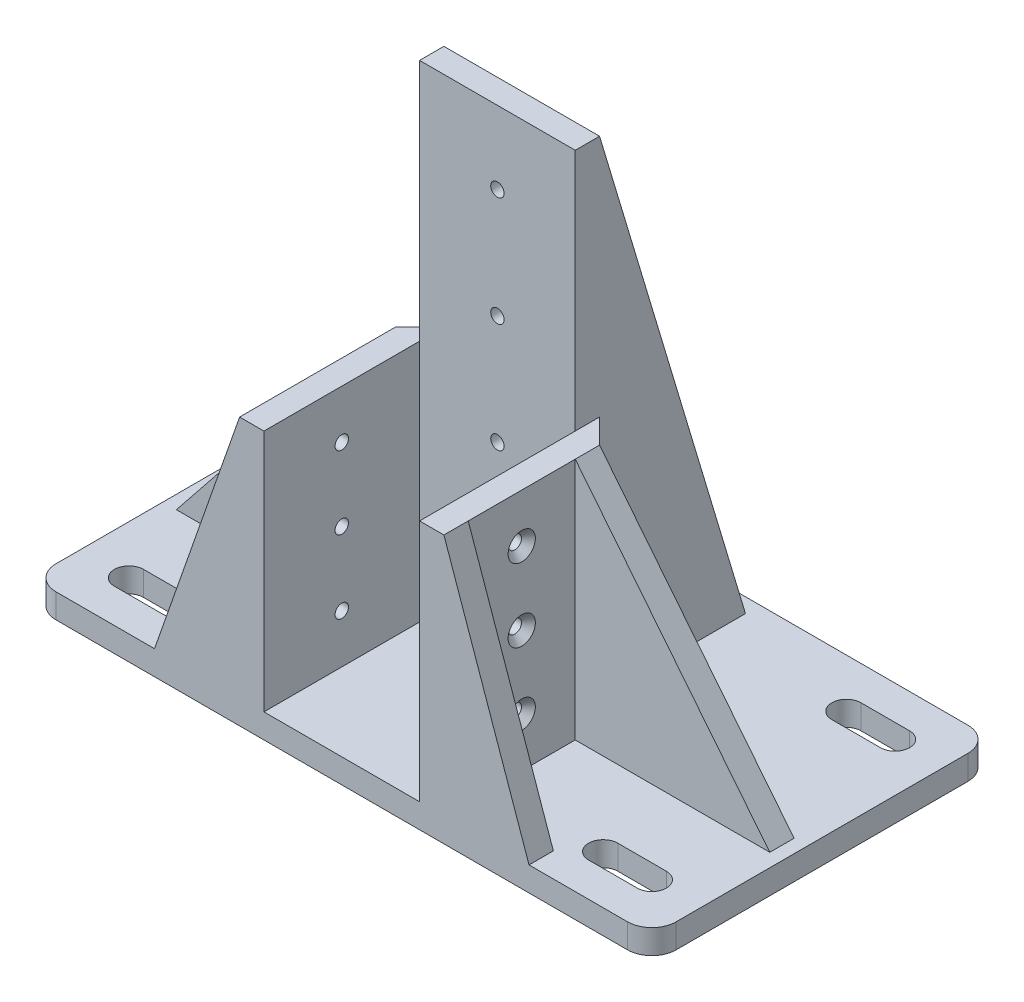
SolidWorks part; units mm, degrees
material "1060 合金"
ref_plane "前视基准面" through (0, 0, 0) normal (0, 0, 1) x (1, 0, 0)
ref_plane "上视基准面" through (0, 0, 0) normal (0, 1, 0) x (1, 0, 0)
ref_plane "右视基准面" through (0, 0, 0) normal (1, 0, 0) x (0, 0, -1)
sketch "草图1" plane through (0, 0, 0) normal (0, 1, 0) x (1, 0, 0)
  line L0 (-107.5, 50) -> (-87.5, 50) construction
  line L1 (-117.5, 70) -> (117.5, 70)
  line L2 (-127.5, 60) -> (-127.5, -60)
  line L3 (-117.5, -70) -> (117.5, -70)
  line L4 (127.5, 60) -> (127.5, -60)
  line L7 (-107.5, 56) -> (-87.5, 56)
  line L8 (-107.5, 44) -> (-87.5, 44)
  line L9 (0, 0) -> (-135, 0) construction
  line L10 (-107.5, -50) -> (-87.5, -50) construction
  line L11 (-107.5, -56) -> (-87.5, -56)
  line L12 (-107.5, -44) -> (-87.5, -44)
  line L13 (0, 0) -> (0, -60) construction
  line L14 (107.5, -50) -> (87.5, -50) construction
  line L15 (107.5, -56) -> (87.5, -56)
  line L16 (107.5, -44) -> (87.5, -44)
  line L17 (107.5, 50) -> (87.5, 50) construction
  line L18 (107.5, 56) -> (87.5, 56)
  line L19 (107.5, 44) -> (87.5, 44)
  arc A0 (-107.5, 56) -> (-107.5, 44) centre (-107.5, 50) ccw
  arc A1 (-87.5, 44) -> (-87.5, 56) centre (-87.5, 50) ccw
  arc A2 (-107.5, -56) -> (-107.5, -44) centre (-107.5, -50) cw
  arc A3 (-87.5, -44) -> (-87.5, -56) centre (-87.5, -50) cw
  arc A4 (107.5, -56) -> (107.5, -44) centre (107.5, -50) ccw
  arc A5 (87.5, -44) -> (87.5, -56) centre (87.5, -50) ccw
  arc A6 (107.5, 56) -> (107.5, 44) centre (107.5, 50) cw
  arc A7 (87.5, 44) -> (87.5, 56) centre (87.5, 50) cw
  arc A8 (117.5, 70) -> (127.5, 60) centre (117.5, 60) cw
  arc A9 (117.5, -70) -> (127.5, -60) centre (117.5, -60) ccw
  arc A10 (-127.5, -60) -> (-117.5, -70) centre (-117.5, -60) ccw
  arc A11 (-117.5, 70) -> (-127.5, 60) centre (-117.5, 60) ccw
  point P0 (0, 0)
  point P8 (-97.5, 50)
  point P17 (-97.5, -50)
  point P26 (97.5, -50)
  point P33 (97.5, 50)
  point P50 (0, 0)
  dimension "D3" = 6
  dimension "D5" = 20
  dimension "D7" = 10
  dimension "D9" = 20
  dimension "D8" = 20
  dimension "D1" = 100
  dimension "D2" = 175
  dimension "D4" = 20
  dimension "D6" = 20
extrude "立臂底座" add sketch "草图1" along normal blind 10
sketch "草图2" plane through (0, 10, 0) normal (0, 1, 0) x (1, 0, 0)
  line L0 (-42, -70) -> (-32, -70)
  line L1 (-117.5, -70) -> (117.5, -70) construction
  line L2 (-32, -70) -> (-32, -6)
  line L3 (-32, -6) -> (32, -6)
  line L4 (32, -6) -> (32, -70)
  line L5 (32, -70) -> (42, -70)
  line L6 (42, -70) -> (42, -6)
  line L7 (42, -6) -> (32, 4)
  line L8 (32, 4) -> (-32, 4)
  line L9 (-32, 4) -> (-42, -6)
  line L10 (-42, -6) -> (-42, -70)
  line L11 (0, -2.5516) -> (0, 45.157) construction
  dimension "D1" = 10
  dimension "D2" = 10
  dimension "D3" = 10
  dimension "D4" = 64
  dimension "D5" = 64
  dimension "D6" = 32
extrude "包围支撑" add sketch "草图2" along normal blind 100
sketch "草图3" plane through (0, 110, 0) normal (0, 1, 0) x (1, 0, 0)
  line L0 (-32, -6) -> (-32, 4)
  line L1 (32, -6) -> (32, 4)
  line L10 (-42, -6) -> (-42, -70)
  line L11 (-42, -70) -> (-32, -70)
  line L12 (-32, -70) -> (-32, -6)
  line L13 (-32, -6) -> (32, -6)
  line L14 (32, -6) -> (32, -70)
  line L15 (32, -70) -> (42, -70)
  line L16 (42, -70) -> (42, -6)
  line L17 (42, -6) -> (32, 4)
  line L18 (32, 4) -> (-32, 4)
  line L19 (-32, 4) -> (-42, -6)
  line L23 (-32, -6) -> (32, -6)
  line L28 (32, 4) -> (-32, 4)
  dimension "D1" = 0
extrude "后支撑" add sketch "草图3" along normal blind 100
sketch "草图4" plane through (0, 0, 70) normal (0, 0, 1) x (1, 0, 0)
  line L0 (-42, 110) -> (-42, 10) construction
  line L1 (-42, 110) -> (-42, 10)
  line L2 (-117.5, 10) -> (-42, 10) construction
  line L3 (-42, 110) -> (-77, 10)
  line L4 (-77, 10) -> (-42, 10)
  dimension "D1" = 35
extrude "侧支撑 - 小" add sketch "草图4" against normal blind 10
sketch "草图6" plane through (0, 0, 6) normal (0, 0, 1) x (1, 0, 0)
  line L0 (-32, 110) -> (-32, 10) construction
  line L1 (-32, 110) -> (-32, 10)
  line L2 (-42, 110) -> (-122, 10)
  line L3 (-32, 110) -> (-42, 110)
  line L4 (-32, 110) -> (-32, 10)
  line L5 (-32, 10) -> (-42, 10)
  line L6 (-42, 110) -> (-42, 10)
  line L7 (-122, 10) -> (-42, 10)
  dimension "D1" = 10
  dimension "D2" = 80
extrude "侧支撑 - 大" add sketch "草图6" along normal blind 10 contours L2 L7 L6
sketch "草图7" plane through (-32, 0, 0) normal (-1, 0, 0) x (0, 0, 1)
  line L2 (-4, 210) -> (-4, 10)
  line L3 (-4, 10) -> (-64, 10)
  line L4 (-64, 10) -> (-4, 210)
  dimension "D1" = 60
extrude "后置撑 - 筋" add sketch "草图7" against normal blind 10
hole_wizard "M5*3 沉头孔 - 侧面" positions "草图10" profile "草图11" countersink size "M5" standard "ISO"
sketch "草图10" plane through (-42, 0, 0) normal (-1, 0, 0) x (0, 0, 1)
  line L0 (16, 110) -> (60, 110) construction
  line L2 (16, 110) -> (16, 10) construction
  point P0 (38, 90)
  point P18 (38, 60)
  point P19 (38, 30)
  dimension "D1" = 20
  dimension "D2" = 22
  dimension "D3" = 3
sketch "草图11" plane through (-42, 90, 38) normal (0, 1, 0) x (0, 0, 1)
  line L0 (0, 0) -> (0, 84)
  line L1 (0, 84) -> (2.75, 84)
  line L2 (2.75, 84) -> (2.75, 2.85)
  line L3 (2.75, 2.85) -> (5.6, 0)
  line L5 (5.6, 0) -> (0, 0)
  line L6 (-2.75, 2.85) -> (-5.6, 0) construction
  line L11 (0, -6.35) -> (0, 107.95) construction
  dimension "通孔孔直径" = 5.5
  dimension "通孔孔深度" = 84
  dimension "近端锥形沉头孔直径" = 11.2
  dimension "近端锥形沉头孔角度" = 90
mirror "支撑筋镜像" about plane through (0, 0, 0) normal (1, 0, 0) of "M5*3 沉头孔 - 侧面", "后置撑 - 筋", "侧支撑 - 大", "侧支撑 - 小"
hole_wizard "M5*4 沉头孔 - 后面" positions "草图13" profile "草图14" countersink size "M5" standard "ISO" end condition up to next
sketch "草图13" plane through (0, 0, -4) normal (0, 0, -1) x (-1, 0, 0)
  line L0 (-22, 210) -> (22, 210) construction
  point P0 (0, 180)
  point P10 (0, 135)
  point P11 (0, 90)
  point P12 (0, 45)
  dimension "D1" = 30
  dimension "D2" = 4
sketch "草图14" plane through (0, 180, -4) normal (1, 0, 0) x (0, 1, 0)
  line L0 (0, 0) -> (0, 10)
  line L1 (0, 10) -> (2.75, 10)
  line L2 (2.75, 10) -> (2.75, 2.85)
  line L3 (2.75, 2.85) -> (5.6, 0)
  line L5 (5.6, 0) -> (0, 0)
  line L6 (-2.75, 2.85) -> (-5.6, 0) construction
  line L11 (0, -6.35) -> (0, 107.95) construction
  dimension "通孔孔直径" = 5.5
  dimension "通孔孔深度" = 10
  dimension "近端锥形沉头孔直径" = 11.2
  dimension "近端锥形沉头孔角度" = 90
